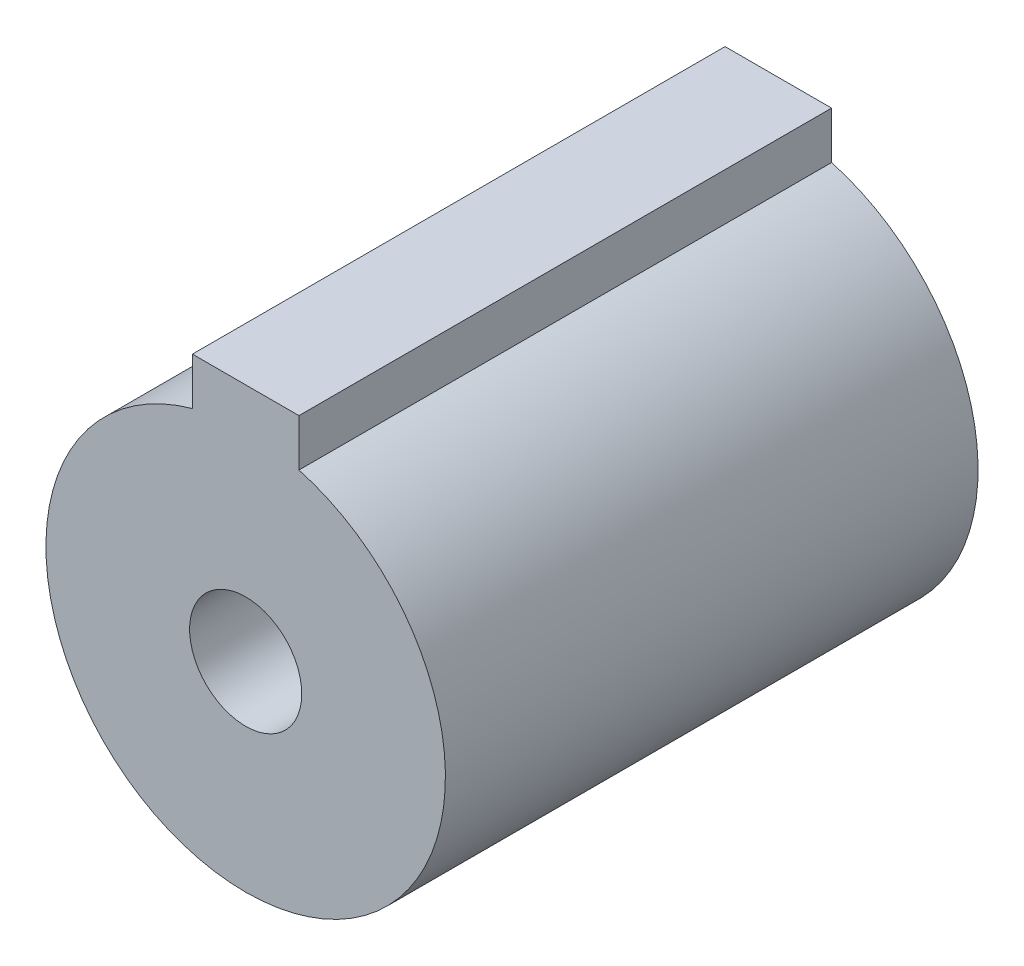
SolidWorks part; units mm, degrees
ref_plane "Front Plane" through (0, 0, 0) normal (0, 0, 1) x (1, 0, 0)
ref_plane "Top Plane" through (0, 0, 0) normal (0, 1, 0) x (1, 0, 0)
ref_plane "Right Plane" through (0, 0, 0) normal (1, 0, 0) x (0, 0, -1)
sketch "Sketch1" plane through (0, 0, 0) normal (0, 0, 1) x (1, 0, 0)
  line L3 (4, 17.9968) -> (-4, 17.9968)
  line L7 (-4, 14.4568) -> (-4, 17.9968)
  line L8 (4, 14.4568) -> (4, 17.9968)
  arc A0 (-4, 14.4568) -> (4, 14.4568) centre (0, 0) ccw
  dimension "D1" = 8
  dimension "D2" = 30
  dimension "D3" = 3.54
extrude "Boss-Extrude1" add sketch "Sketch1" along normal blind 40
sketch "Sketch2" plane through (0, 0, 40) normal (0, 0, 1) x (1, 0, 0)
  circle A0 centre (0, 0) radius 4.21
  dimension "D1" = 8.42
extrude "Cut-Extrude1" cut sketch "Sketch2" against normal blind 40 contours A0
ref_plane "Plane1" through (0, 0, -35) normal (0, 0, 1) x (1, 0, 0)
sketch "Sketch5" plane through (0, 0, -35) normal (0, 0, 1) x (1, 0, 0)
  line L0 (0, -28.1243) -> (0, 28.1243) construction
  line L1 (46.1036, 0) -> (-46.1036, 0) construction
  point P5 (0, 0)
  point P9 (0, 0)
